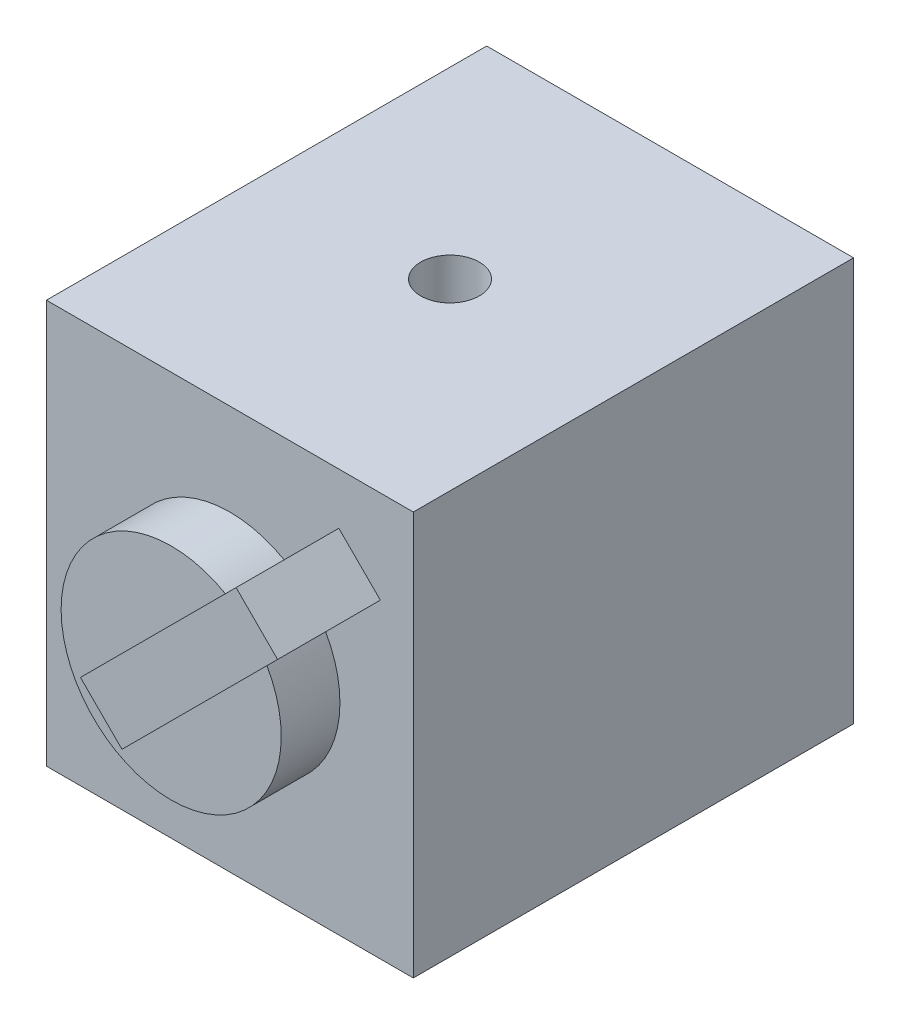
SolidWorks part; units mm, degrees
ref_plane "前视基准面" through (0, 0, 0) normal (0, 0, 1) x (1, 0, 0)
ref_plane "上视基准面" through (0, 0, 0) normal (0, 1, 0) x (1, 0, 0)
ref_plane "右视基准面" through (0, 0, 0) normal (1, 0, 0) x (0, 0, -1)
sketch "草图1" plane through (0, 0, 0) normal (0, 0, 1) x (1, 0, 0)
  line L1 (25, -27.5) -> (-25, -27.5)
  line L2 (25, -27.5) -> (25, 27.5)
  line L3 (25, 27.5) -> (-25, 27.5)
  line L4 (-25, -27.5) -> (-25, 27.5)
  line L5 (25, -27.5) -> (-25, 27.5) construction
  line L6 (25, 27.5) -> (-25, -27.5) construction
  point P0 (0, 0)
  dimension "D1" = 55
  dimension "D2" = 50
extrude "凸台-拉伸1" add sketch "草图1" along normal mid plane 60
sketch "草图2" plane through (0, 0, 30) normal (0, 0, 1) x (1, 0, 0)
  circle A0 centre (0, 0) radius 15
  dimension "D1" = 30
extrude "凸台-拉伸2" add sketch "草图2" along normal blind 8
sketch "草图3" plane through (0, 0, 38) normal (0, 0, 1) x (1, 0, 0)
  line L0 (14.8492, 20.5061) -> (-6.364, -0.7071)
  line L1 (-6.364, -0.7071) -> (-0.7071, -6.364)
  line L2 (-0.7071, -6.364) -> (20.5061, 14.8492)
  line L3 (20.5061, 14.8492) -> (14.8492, 20.5061)
  line L4 (-3.5355, -3.5355) -> (17.6777, 17.6777) construction
  line L5 (-25, -27.5) -> (25, -27.5) construction
  dimension "D1" = 30
  dimension "D2" = 5
  dimension "D3" = 8
  dimension "D4" = 45
extrude "凸台-拉伸3" add sketch "草图3" along normal blind 6 and the other way up to next
sketch "草图4" plane through (0, 27.5, 0) normal (0, 1, 0) x (1, 0, 0)
  circle A0 centre (0, 0) radius 4
  dimension "D1" = 8
extrude "切除-拉伸1" cut sketch "草图4" against normal blind 6
